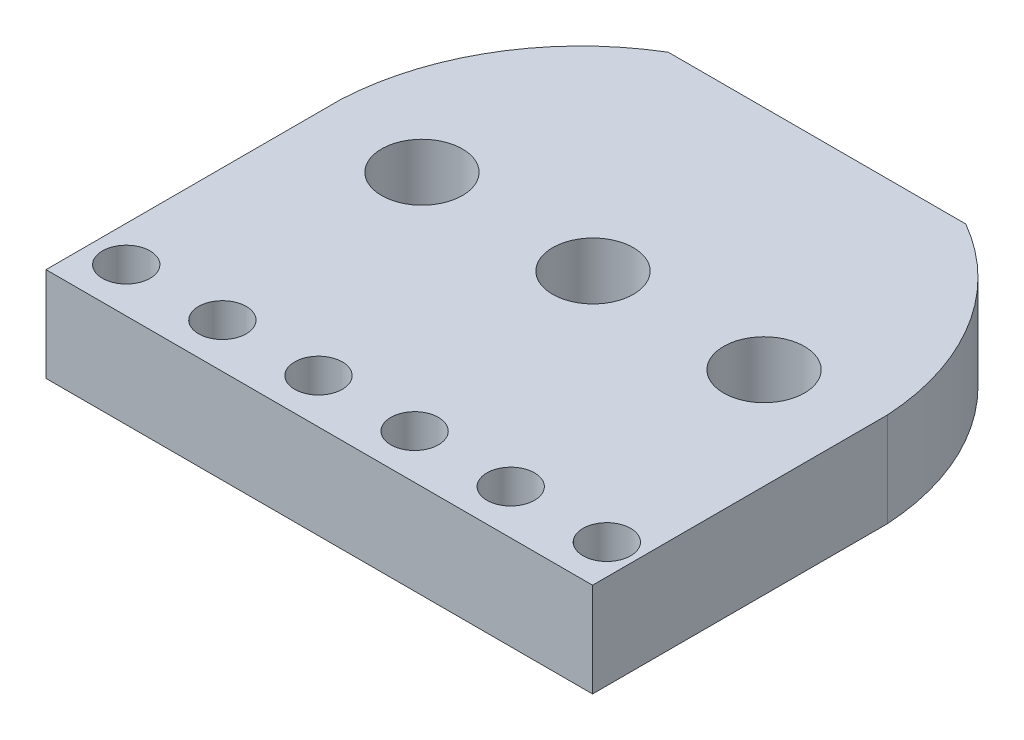
SolidWorks part; units mm, degrees
ref_plane "Front Plane" through (0, 0, 0) normal (0, 0, 1) x (1, 0, 0)
ref_plane "Top Plane" through (0, 0, 0) normal (0, 1, 0) x (1, 0, 0)
ref_plane "Right Plane" through (0, 0, 0) normal (1, 0, 0) x (0, 0, -1)
sketch "Sketch1" plane through (0, 0, 0) normal (0, 1, 0) x (1, 0, 0)
  line L1 (-5.8, -5.3) -> (5.8, -5.3)
  line L2 (-5.8, -5.3) -> (-5.8, 5.3)
  line L3 (-5.8, 5.3) -> (5.8, 5.3)
  line L4 (5.8, -5.3) -> (5.8, 5.3)
  line L5 (-5.8, -5.3) -> (5.8, 5.3) construction
  line L6 (-5.8, 5.3) -> (5.8, -5.3) construction
  point P0 (0, 0)
  dimension "D1" = 11.6
  dimension "D2" = 10.6
extrude "Boss-Extrude1" add sketch "Sketch1" along normal blind 2
sketch "Sketch2" plane through (0, 2, 0) normal (0, 1, 0) x (1, 0, 0)
  line L0 (-5.8, 5.3) -> (-5.8, -5.3) construction
  line L1 (5.8, 5.3) -> (-5.8, 5.3) construction
  line L2 (5.8, -5.3) -> (5.8, 5.3) construction
  line L3 (-5.8, 0.9601) -> (-5.8, 5.3)
  line L4 (-5.8, 5.3) -> (-3.1915, 5.3)
  line L5 (3.1204, 5.3) -> (5.8, 5.3)
  line L6 (5.8, 5.3) -> (5.8, 0.9601)
  arc A0 (-5.8, 0.9601) -> (-3.1915, 5.3) centre (-0.4372, 0.6906) cw
  arc A1 (3.1204, 5.3) -> (5.8, 0.9601) centre (0.4395, 0.6475) cw
  circle A2 centre (-3.6005, 0.4801) radius 0.8581
  circle A3 centre (0.0295, 0.4801) radius 0.8581
  circle A4 centre (3.6595, 0.4801) radius 0.8581
  circle A5 centre (-5.0406, -4.3561) radius 0.5054
  circle A6 centre (-3.0006, -4.3561) radius 0.5054
  circle A7 centre (-0.9606, -4.3561) radius 0.5054
  circle A8 centre (1.0794, -4.3561) radius 0.5054
  circle A9 centre (3.1194, -4.3561) radius 0.5054
  circle A10 centre (5.1594, -4.3561) radius 0.5054
  dimension "D1" = 3
  dimension "D2" = 6
extrude "Cut-Extrude1" cut sketch "Sketch2" against normal through all
